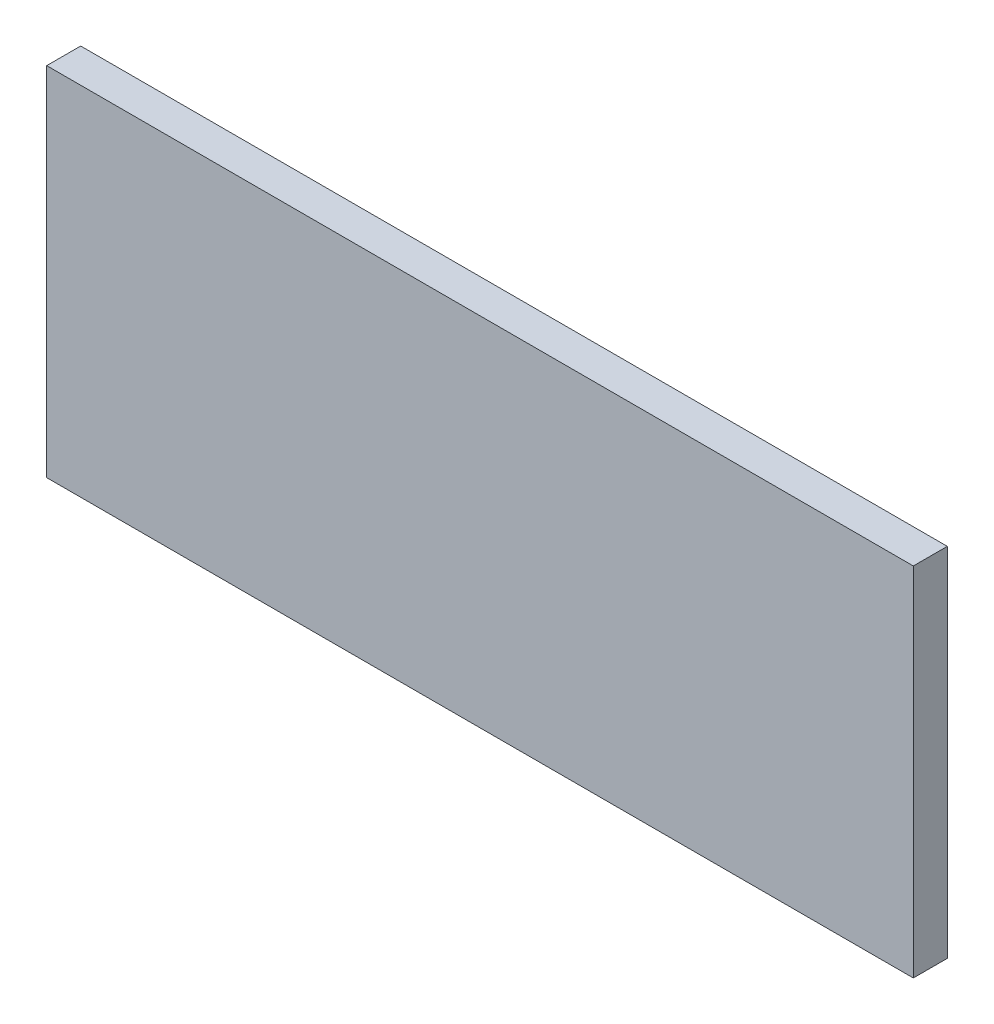
SolidWorks part; units mm, degrees
ref_plane "Front Plane" through (0, 0, 0) normal (0, 0, 1) x (1, 0, 0)
ref_plane "Top Plane" through (0, 0, 0) normal (0, 1, 0) x (1, 0, 0)
ref_plane "Right Plane" through (0, 0, 0) normal (1, 0, 0) x (0, 0, -1)
sketch "Sketch2" plane through (0, 0, 0) normal (0, 0, 1) x (1, 0, 0)
  line L1 (-51, 21) -> (51, 21)
  line L2 (-51, 21) -> (-51, -21)
  line L3 (-51, -21) -> (51, -21)
  line L4 (51, 21) -> (51, -21)
  line L5 (-51, 21) -> (51, -21) construction
  line L6 (-51, -21) -> (51, 21) construction
  point P0 (0, 0)
  dimension "D1" = 42
  dimension "D2" = 102
extrude "Boss-Extrude1" add sketch "Sketch2" along normal blind 4
